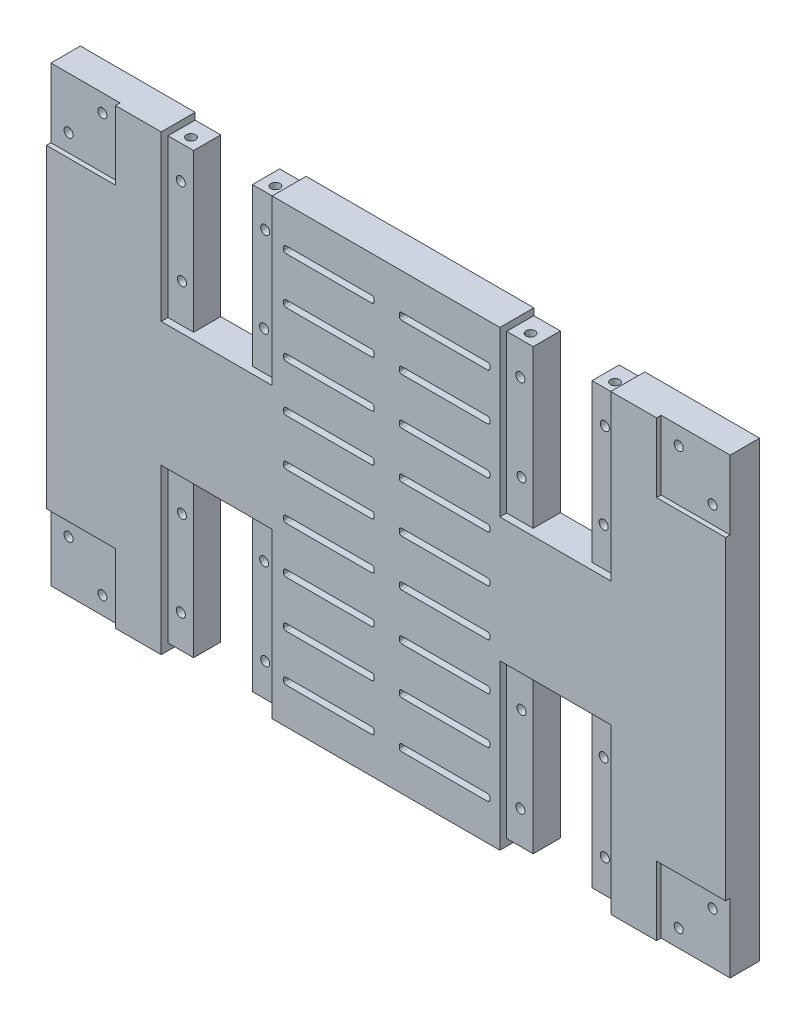
SolidWorks part; units mm, degrees
ref_plane "Alzado" through (0, 0, 0) normal (0, 0, 1) x (1, 0, 0)
ref_plane "Planta" through (0, 0, 0) normal (0, 1, 0) x (1, 0, 0)
ref_plane "Vista lateral" through (0, 0, 0) normal (1, 0, 0) x (0, 0, -1)
sketch "Croquis1" plane through (0, 0, 0) normal (0, 0, 1) x (1, 0, 0)
  line L1 (150, 100) -> (-150, 100)
  line L2 (150, 100) -> (150, -100)
  line L3 (150, -100) -> (-150, -100)
  line L4 (-150, 100) -> (-150, -100)
  line L5 (150, 100) -> (-150, -100) construction
  line L6 (150, -100) -> (-150, 100) construction
  point P0 (0, 0)
  dimension "D1" = 300
  dimension "D2" = 200
extrude "Saliente-Extruir1" add sketch "Croquis1" along normal blind 15
sketch "Croquis2" plane through (0, 0, 15) normal (0, 0, 1) x (1, 0, 0)
  line L0 (0, 0) -> (0, 100) construction
  line L1 (-150, 100) -> (-119.5, 100)
  line L2 (-150, 100) -> (-150, 69.5)
  line L3 (-150, 69.5) -> (-119.5, 69.5)
  line L4 (-119.5, 100) -> (-119.5, 69.5)
  line L5 (150, 100) -> (-150, 100) construction
  line L6 (0, 0) -> (150, 0) construction
  line L7 (150, -100) -> (150, 100) construction
  line L8 (150, 69.5) -> (119.5, 69.5)
  line L9 (119.5, 100) -> (119.5, 69.5)
  line L10 (150, 100) -> (119.5, 100)
  line L11 (150, 100) -> (150, 69.5)
  line L12 (150, -100) -> (150, -69.5)
  line L13 (150, -100) -> (119.5, -100)
  line L14 (119.5, -100) -> (119.5, -69.5)
  line L15 (150, -69.5) -> (119.5, -69.5)
  line L16 (-150, -69.5) -> (-119.5, -69.5)
  line L17 (-119.5, -100) -> (-119.5, -69.5)
  line L18 (-150, -100) -> (-119.5, -100)
  line L19 (-150, -100) -> (-150, -69.5)
  dimension "D1" = 30.5
extrude "Huecos columna" cut sketch "Croquis2" against normal blind 2
sketch "Croquis3" plane through (0, 0, 15) normal (0, 0, 1) x (1, 0, 0)
  line L0 (-119.5, -100) -> (119.5, -100) construction
  line L2 (-88, -97) -> (-88, -27.5)
  line L3 (-88, -27.5) -> (-62, -27.5)
  line L4 (-62, -97) -> (-62, -27.5)
  line L5 (0, 0) -> (0, -100) construction
  line L6 (0, 0) -> (-150, 0) construction
  line L7 (-150, 69.5) -> (-150, -69.5) construction
  line L8 (-88, -58.2044) -> (-150, -58.2044) construction
  line L9 (-62, -60.8904) -> (0, -60.8904) construction
  line L10 (88, -27.5) -> (62, -27.5)
  line L11 (62, -97) -> (62, -27.5)
  line L13 (88, -97) -> (88, -27.5)
  line L14 (88, 97) -> (88, 27.5)
  line L16 (62, 97) -> (62, 27.5)
  line L17 (88, 27.5) -> (62, 27.5)
  line L18 (-88, 27.5) -> (-62, 27.5)
  line L19 (-62, 97) -> (-62, 27.5)
  line L21 (-88, 97) -> (-88, 27.5)
  line L22 (-99.2954, -100) -> (-50.2954, -100)
  line L24 (-99.2954, -100) -> (-99.2954, -97)
  line L25 (-99.2954, -97) -> (-88, -97)
  line L26 (-50.2954, -100) -> (-50.2954, -97)
  line L27 (99.2954, -100) -> (50.2954, -100)
  line L28 (50.2954, -100) -> (50.2954, -97)
  line L29 (99.2954, -97) -> (88, -97)
  line L30 (99.2954, -100) -> (99.2954, -97)
  line L31 (99.2954, 100) -> (99.2954, 97)
  line L32 (99.2954, 97) -> (88, 97)
  line L33 (50.2954, 100) -> (50.2954, 97)
  line L34 (99.2954, 100) -> (50.2954, 100)
  line L35 (-99.2954, 100) -> (-50.2954, 100)
  line L36 (-50.2954, 100) -> (-50.2954, 97)
  line L37 (-99.2954, 97) -> (-88, 97)
  line L38 (-99.2954, 100) -> (-99.2954, 97)
  line L39 (-62, -97) -> (-50.2954, -97)
  line L40 (62, -97) -> (50.2954, -97)
  line L41 (62, 97) -> (50.2954, 97)
  line L42 (-62, 97) -> (-50.2954, 97)
  point P28 (-75, -100)
  point P36 (-74.7954, -100)
  dimension "D1" = 26
  dimension "D2" = 49
  dimension "D3" = 3
  dimension "D4" = 69.5
extrude "huecos  motor" cut sketch "Croquis3" against normal through all
sketch "Croquis4" plane through (0, -97, 0) normal (0, -1, 0) x (1, 0, 0)
  line L0 (-99.2954, 15) -> (-88, 0) construction
  line L1 (-88, 0) -> (-88, 15) construction
  line L2 (-88, 15) -> (-99.2954, 0) construction
  line L3 (0, 0) -> (0, 15) construction
  line L4 (-50.2954, 15) -> (50.2954, 15) construction
  line L5 (-75, 15) -> (-75, 0) construction
  line L6 (-62, 15) -> (-88, 15) construction
  line L7 (-62, 0) -> (-88, 0) construction
  circle A0 centre (-93.6477, 7.5) radius 2
  circle A1 centre (-56.3523, 7.5) radius 2
  circle A2 centre (56.3523, 7.5) radius 2
  circle A3 centre (93.6477, 7.5) radius 2
extrude "side_screws 1" cut sketch "Croquis4" against normal blind 15
sketch "Croquis5" plane through (0, 97, 0) normal (0, 1, 0) x (1, 0, 0)
  line L0 (-99.2954, 0) -> (-88, -15) construction
  line L1 (-88, -15) -> (-88, 0) construction
  line L2 (-88, 0) -> (-99.2954, -15) construction
  line L3 (-75, 0) -> (-75, -15) construction
  line L4 (-88, 0) -> (-62, 0) construction
  line L5 (-88, -15) -> (-62, -15) construction
  line L6 (0, 0) -> (0, -15) construction
  line L7 (50.2954, -15) -> (-50.2954, -15) construction
  circle A0 centre (-93.6477, -7.5) radius 2
  circle A1 centre (-56.3523, -7.5) radius 2
  circle A2 centre (56.3523, -7.5) radius 2
  circle A3 centre (93.6477, -7.5) radius 2
extrude "side screws 2" cut sketch "Croquis5" against normal blind 15
sketch "Croquis7" plane through (0, 0, 15) normal (0, 0, 1) x (1, 0, 0)
  line L0 (-150, -69.5) -> (-119.5, -100) construction
  line L1 (-150, -100) -> (-119.5, -69.5) construction
  line L2 (-150, 0) -> (0, 0) construction
  line L3 (-150, 69.5) -> (-150, -69.5) construction
  line L4 (0, 0) -> (0, -100) construction
  line L5 (-50.2954, -100) -> (50.2954, -100) construction
  line L6 (6.8759, 84) -> (44.8759, 84)
  line L7 (-44.236, 81) -> (-6.236, 81)
  line L8 (-45.236, 82) -> (-45.236, 83)
  line L9 (-44.236, 84) -> (-6.236, 84)
  line L10 (-5.236, 82) -> (-5.236, 83)
  line L11 (-45.236, 81) -> (-5.236, 84) construction
  line L12 (-45.236, 84) -> (-5.236, 81) construction
  line L13 (6.8759, 81) -> (44.8759, 81)
  line L14 (5.8759, 82) -> (5.8759, 83)
  line L15 (45.8759, 82) -> (45.8759, 83)
  line L16 (6.8759, 63.375) -> (44.8759, 63.375)
  line L17 (6.8759, 60.375) -> (44.8759, 60.375)
  line L18 (5.8759, 61.375) -> (5.8759, 62.375)
  line L19 (45.8759, 61.375) -> (45.8759, 62.375)
  line L20 (6.8759, 42.75) -> (44.8759, 42.75)
  line L21 (6.8759, 39.75) -> (44.8759, 39.75)
  line L22 (5.8759, 40.75) -> (5.8759, 41.75)
  line L23 (45.8759, 40.75) -> (45.8759, 41.75)
  line L24 (6.8759, 22.125) -> (44.8759, 22.125)
  line L25 (6.8759, 19.125) -> (44.8759, 19.125)
  line L26 (5.8759, 20.125) -> (5.8759, 21.125)
  line L27 (45.8759, 20.125) -> (45.8759, 21.125)
  line L28 (6.8759, 1.5) -> (44.8759, 1.5)
  line L29 (6.8759, -1.5) -> (44.8759, -1.5)
  line L30 (5.8759, -0.5) -> (5.8759, 0.5)
  line L31 (45.8759, -0.5) -> (45.8759, 0.5)
  line L32 (6.8759, -19.125) -> (44.8759, -19.125)
  line L33 (6.8759, -22.125) -> (44.8759, -22.125)
  line L34 (5.8759, -21.125) -> (5.8759, -20.125)
  line L35 (45.8759, -21.125) -> (45.8759, -20.125)
  line L36 (6.8759, -39.75) -> (44.8759, -39.75)
  line L37 (6.8759, -42.75) -> (44.8759, -42.75)
  line L38 (5.8759, -41.75) -> (5.8759, -40.75)
  line L39 (45.8759, -41.75) -> (45.8759, -40.75)
  line L40 (6.8759, -60.375) -> (44.8759, -60.375)
  line L41 (6.8759, -63.375) -> (44.8759, -63.375)
  line L42 (5.8759, -62.375) -> (5.8759, -61.375)
  line L43 (45.8759, -62.375) -> (45.8759, -61.375)
  line L44 (6.8759, -81) -> (44.8759, -81)
  line L45 (6.8759, -84) -> (44.8759, -84)
  line L46 (5.8759, -83) -> (5.8759, -82)
  line L47 (45.8759, -83) -> (45.8759, -82)
  line L48 (-44.236, 63.375) -> (-6.236, 63.375)
  line L49 (-44.236, 60.375) -> (-6.236, 60.375)
  line L50 (-45.236, 61.375) -> (-45.236, 62.375)
  line L51 (-5.236, 61.375) -> (-5.236, 62.375)
  line L52 (-44.236, 42.75) -> (-6.236, 42.75)
  line L53 (-44.236, 39.75) -> (-6.236, 39.75)
  line L54 (-45.236, 40.75) -> (-45.236, 41.75)
  line L55 (-5.236, 40.75) -> (-5.236, 41.75)
  line L56 (-44.236, 22.125) -> (-6.236, 22.125)
  line L57 (-44.236, 19.125) -> (-6.236, 19.125)
  line L58 (-45.236, 20.125) -> (-45.236, 21.125)
  line L59 (-5.236, 20.125) -> (-5.236, 21.125)
  line L60 (-44.236, 1.5) -> (-6.236, 1.5)
  line L61 (-44.236, -1.5) -> (-6.236, -1.5)
  line L62 (-45.236, -0.5) -> (-45.236, 0.5)
  line L63 (-5.236, -0.5) -> (-5.236, 0.5)
  line L64 (-44.236, -19.125) -> (-6.236, -19.125)
  line L65 (-44.236, -22.125) -> (-6.236, -22.125)
  line L66 (-45.236, -21.125) -> (-45.236, -20.125)
  line L67 (-5.236, -21.125) -> (-5.236, -20.125)
  line L68 (-44.236, -39.75) -> (-6.236, -39.75)
  line L69 (-44.236, -42.75) -> (-6.236, -42.75)
  line L70 (-45.236, -41.75) -> (-45.236, -40.75)
  line L71 (-5.236, -41.75) -> (-5.236, -40.75)
  line L72 (-44.236, -60.375) -> (-6.236, -60.375)
  line L73 (-44.236, -63.375) -> (-6.236, -63.375)
  line L74 (-45.236, -62.375) -> (-45.236, -61.375)
  line L75 (-5.236, -62.375) -> (-5.236, -61.375)
  line L76 (-44.236, -81) -> (-6.236, -81)
  line L77 (-44.236, -84) -> (-6.236, -84)
  line L78 (-45.236, -83) -> (-45.236, -82)
  line L79 (-5.236, -83) -> (-5.236, -82)
  line L80 (39.4634, 84) -> (39.4634, 100) construction
  line L81 (50.2954, 100) -> (-50.2954, 100) construction
  line L82 (-93.6477, -97) -> (-93.6477, -82.5) construction
  line L83 (25.8759, -84) -> (25.8759, -100) construction
  line L84 (-45.236, 82.5) -> (-56.3523, 82.5) construction
  line L85 (-5.236, 82.8086) -> (5.8759, 82.5) construction
  line L87 (45.8759, 82.5) -> (62, 82.5) construction
  line L88 (62, 97) -> (62, 27.5) construction
  line L89 (-88, -97) -> (-99.2954, -97) construction
  line L90 (-75, -27.5) -> (-75, -100) construction
  line L91 (-62, -27.5) -> (-88, -27.5) construction
  line L92 (-56.3523, -97) -> (-56.3523, -82.5) construction
  line L93 (56.3523, -97) -> (56.3523, -82.5) construction
  line L94 (93.6477, -97) -> (93.6477, -82.5) construction
  line L95 (93.6477, 97) -> (93.6477, 82.5) construction
  line L96 (56.3523, 97) -> (56.3523, 82.5) construction
  line L97 (-56.3523, 97) -> (-56.3523, 82.5) construction
  line L98 (-93.6477, 97) -> (-93.6477, 82.5) construction
  circle A0 centre (-127.2782, -92.2218) radius 2
  circle A1 centre (-142.2218, -77.2782) radius 2
  circle A2 centre (-127.2782, 92.2218) radius 2
  circle A3 centre (-142.2218, 77.2782) radius 2
  circle A4 centre (127.2782, -92.2218) radius 2
  circle A5 centre (142.2218, -77.2782) radius 2
  circle A6 centre (127.2782, 92.2218) radius 2
  circle A7 centre (142.2218, 77.2782) radius 2
  arc A8 (-5.236, 82) -> (-6.236, 81) centre (-6.236, 82) cw
  arc A9 (-5.236, 83) -> (-6.236, 84) centre (-6.236, 83) ccw
  arc A10 (-44.236, 81) -> (-45.236, 82) centre (-44.236, 82) cw
  arc A11 (-45.236, 83) -> (-44.236, 84) centre (-44.236, 83) cw
  arc A12 (5.8759, 83) -> (6.8759, 84) centre (6.8759, 83) cw
  arc A13 (6.8759, 81) -> (5.8759, 82) centre (6.8759, 82) cw
  arc A14 (45.8759, 83) -> (44.8759, 84) centre (44.8759, 83) ccw
  arc A15 (45.8759, 82) -> (44.8759, 81) centre (44.8759, 82) cw
  arc A16 (5.8759, 62.375) -> (6.8759, 63.375) centre (6.8759, 62.375) cw
  arc A17 (6.8759, 60.375) -> (5.8759, 61.375) centre (6.8759, 61.375) cw
  arc A18 (45.8759, 62.375) -> (44.8759, 63.375) centre (44.8759, 62.375) ccw
  arc A19 (45.8759, 61.375) -> (44.8759, 60.375) centre (44.8759, 61.375) cw
  arc A20 (5.8759, 41.75) -> (6.8759, 42.75) centre (6.8759, 41.75) cw
  arc A21 (6.8759, 39.75) -> (5.8759, 40.75) centre (6.8759, 40.75) cw
  arc A22 (45.8759, 41.75) -> (44.8759, 42.75) centre (44.8759, 41.75) ccw
  arc A23 (45.8759, 40.75) -> (44.8759, 39.75) centre (44.8759, 40.75) cw
  arc A24 (5.8759, 21.125) -> (6.8759, 22.125) centre (6.8759, 21.125) cw
  arc A25 (6.8759, 19.125) -> (5.8759, 20.125) centre (6.8759, 20.125) cw
  arc A26 (45.8759, 21.125) -> (44.8759, 22.125) centre (44.8759, 21.125) ccw
  arc A27 (45.8759, 20.125) -> (44.8759, 19.125) centre (44.8759, 20.125) cw
  arc A28 (5.8759, 0.5) -> (6.8759, 1.5) centre (6.8759, 0.5) cw
  arc A29 (6.8759, -1.5) -> (5.8759, -0.5) centre (6.8759, -0.5) cw
  arc A30 (45.8759, 0.5) -> (44.8759, 1.5) centre (44.8759, 0.5) ccw
  arc A31 (45.8759, -0.5) -> (44.8759, -1.5) centre (44.8759, -0.5) cw
  arc A32 (5.8759, -20.125) -> (6.8759, -19.125) centre (6.8759, -20.125) cw
  arc A33 (6.8759, -22.125) -> (5.8759, -21.125) centre (6.8759, -21.125) cw
  arc A34 (45.8759, -20.125) -> (44.8759, -19.125) centre (44.8759, -20.125) ccw
  arc A35 (45.8759, -21.125) -> (44.8759, -22.125) centre (44.8759, -21.125) cw
  arc A36 (5.8759, -40.75) -> (6.8759, -39.75) centre (6.8759, -40.75) cw
  arc A37 (6.8759, -42.75) -> (5.8759, -41.75) centre (6.8759, -41.75) cw
  arc A38 (45.8759, -40.75) -> (44.8759, -39.75) centre (44.8759, -40.75) ccw
  arc A39 (45.8759, -41.75) -> (44.8759, -42.75) centre (44.8759, -41.75) cw
  arc A40 (5.8759, -61.375) -> (6.8759, -60.375) centre (6.8759, -61.375) cw
  arc A41 (6.8759, -63.375) -> (5.8759, -62.375) centre (6.8759, -62.375) cw
  arc A42 (45.8759, -61.375) -> (44.8759, -60.375) centre (44.8759, -61.375) ccw
  arc A43 (45.8759, -62.375) -> (44.8759, -63.375) centre (44.8759, -62.375) cw
  arc A44 (5.8759, -82) -> (6.8759, -81) centre (6.8759, -82) cw
  arc A45 (6.8759, -84) -> (5.8759, -83) centre (6.8759, -83) cw
  arc A46 (45.8759, -82) -> (44.8759, -81) centre (44.8759, -82) ccw
  arc A47 (45.8759, -83) -> (44.8759, -84) centre (44.8759, -83) cw
  arc A48 (-45.236, 62.375) -> (-44.236, 63.375) centre (-44.236, 62.375) cw
  arc A49 (-44.236, 60.375) -> (-45.236, 61.375) centre (-44.236, 61.375) cw
  arc A50 (-5.236, 62.375) -> (-6.236, 63.375) centre (-6.236, 62.375) ccw
  arc A51 (-5.236, 61.375) -> (-6.236, 60.375) centre (-6.236, 61.375) cw
  arc A52 (-45.236, 41.75) -> (-44.236, 42.75) centre (-44.236, 41.75) cw
  arc A53 (-44.236, 39.75) -> (-45.236, 40.75) centre (-44.236, 40.75) cw
  arc A54 (-5.236, 41.75) -> (-6.236, 42.75) centre (-6.236, 41.75) ccw
  arc A55 (-5.236, 40.75) -> (-6.236, 39.75) centre (-6.236, 40.75) cw
  arc A56 (-45.236, 21.125) -> (-44.236, 22.125) centre (-44.236, 21.125) cw
  arc A57 (-44.236, 19.125) -> (-45.236, 20.125) centre (-44.236, 20.125) cw
  arc A58 (-5.236, 21.125) -> (-6.236, 22.125) centre (-6.236, 21.125) ccw
  arc A59 (-5.236, 20.125) -> (-6.236, 19.125) centre (-6.236, 20.125) cw
  arc A60 (-45.236, 0.5) -> (-44.236, 1.5) centre (-44.236, 0.5) cw
  arc A61 (-44.236, -1.5) -> (-45.236, -0.5) centre (-44.236, -0.5) cw
  arc A62 (-5.236, 0.5) -> (-6.236, 1.5) centre (-6.236, 0.5) ccw
  arc A63 (-5.236, -0.5) -> (-6.236, -1.5) centre (-6.236, -0.5) cw
  arc A64 (-45.236, -20.125) -> (-44.236, -19.125) centre (-44.236, -20.125) cw
  arc A65 (-44.236, -22.125) -> (-45.236, -21.125) centre (-44.236, -21.125) cw
  arc A66 (-5.236, -20.125) -> (-6.236, -19.125) centre (-6.236, -20.125) ccw
  arc A67 (-5.236, -21.125) -> (-6.236, -22.125) centre (-6.236, -21.125) cw
  arc A68 (-45.236, -40.75) -> (-44.236, -39.75) centre (-44.236, -40.75) cw
  arc A69 (-44.236, -42.75) -> (-45.236, -41.75) centre (-44.236, -41.75) cw
  arc A70 (-5.236, -40.75) -> (-6.236, -39.75) centre (-6.236, -40.75) ccw
  arc A71 (-5.236, -41.75) -> (-6.236, -42.75) centre (-6.236, -41.75) cw
  arc A72 (-45.236, -61.375) -> (-44.236, -60.375) centre (-44.236, -61.375) cw
  arc A73 (-44.236, -63.375) -> (-45.236, -62.375) centre (-44.236, -62.375) cw
  arc A74 (-5.236, -61.375) -> (-6.236, -60.375) centre (-6.236, -61.375) ccw
  arc A75 (-5.236, -62.375) -> (-6.236, -63.375) centre (-6.236, -62.375) cw
  arc A76 (-45.236, -82) -> (-44.236, -81) centre (-44.236, -82) cw
  arc A77 (-44.236, -84) -> (-45.236, -83) centre (-44.236, -83) cw
  arc A78 (-5.236, -82) -> (-6.236, -81) centre (-6.236, -82) ccw
  arc A79 (-5.236, -83) -> (-6.236, -84) centre (-6.236, -83) cw
  circle A80 centre (-93.6477, -82.5) radius 2
  circle A81 centre (-93.1477, -44.5033) radius 2
  circle A82 centre (-56.3523, -82.5) radius 2
  circle A83 centre (-56.8523, -44.5033) radius 2
  circle A84 centre (56.8523, -44.5033) radius 2
  circle A85 centre (56.3523, -82.5) radius 2
  circle A86 centre (93.6477, -82.5) radius 2
  circle A87 centre (93.1477, -44.5033) radius 2
  circle A88 centre (93.6477, 82.5) radius 2
  circle A89 centre (93.1477, 44.5033) radius 2
  circle A90 centre (56.3523, 82.5) radius 2
  circle A91 centre (56.8523, 44.5033) radius 2
  circle A92 centre (-56.3523, 82.5) radius 2
  circle A93 centre (-56.8523, 44.5033) radius 2
  circle A94 centre (-93.6477, 82.5) radius 2
  circle A95 centre (-93.1477, 44.5033) radius 2
  point P32 (-25.236, 82.5)
  dimension "D1" = 11
  dimension "D4" = 1
  dimension "D8" = 38
  dimension "D2" = 3
  dimension "D3" = 40
  dimension "D7" = 14.5
  dimension "D5" = 2
  dimension "D6" = 9
extrude "screws and venti" cut sketch "Croquis7" against normal blind 15
sketch "Croquis9" plane through (0, 0, 15) normal (0, 0, 1) x (1, 0, 0)
  line L1 (-99.2954, -97) -> (-50.2954, -97)
  line L2 (-99.2954, -97) -> (-99.2954, -27.5)
  line L3 (-99.2954, -27.5) -> (-50.2954, -27.5)
  line L4 (-50.2954, -97) -> (-50.2954, -27.5)
  line L5 (-62, -27.5) -> (-88, -27.5) construction
  line L6 (0, 0) -> (-102.0652, 0) construction
  line L7 (0, 0) -> (0, -97) construction
  line L8 (99.2954, -27.5) -> (50.2954, -27.5)
  line L9 (50.2954, -97) -> (50.2954, -27.5)
  line L10 (99.2954, -97) -> (50.2954, -97)
  line L11 (99.2954, -97) -> (99.2954, -27.5)
  line L12 (99.2954, 97) -> (99.2954, 27.5)
  line L13 (99.2954, 97) -> (50.2954, 97)
  line L14 (50.2954, 97) -> (50.2954, 27.5)
  line L15 (99.2954, 27.5) -> (50.2954, 27.5)
  line L16 (-99.2954, 27.5) -> (-50.2954, 27.5)
  line L17 (-50.2954, 97) -> (-50.2954, 27.5)
  line L18 (-99.2954, 97) -> (-50.2954, 97)
  line L19 (-99.2954, 97) -> (-99.2954, 27.5)
extrude "Cortar-Extruir6" cut sketch "Croquis9" against normal blind 3
